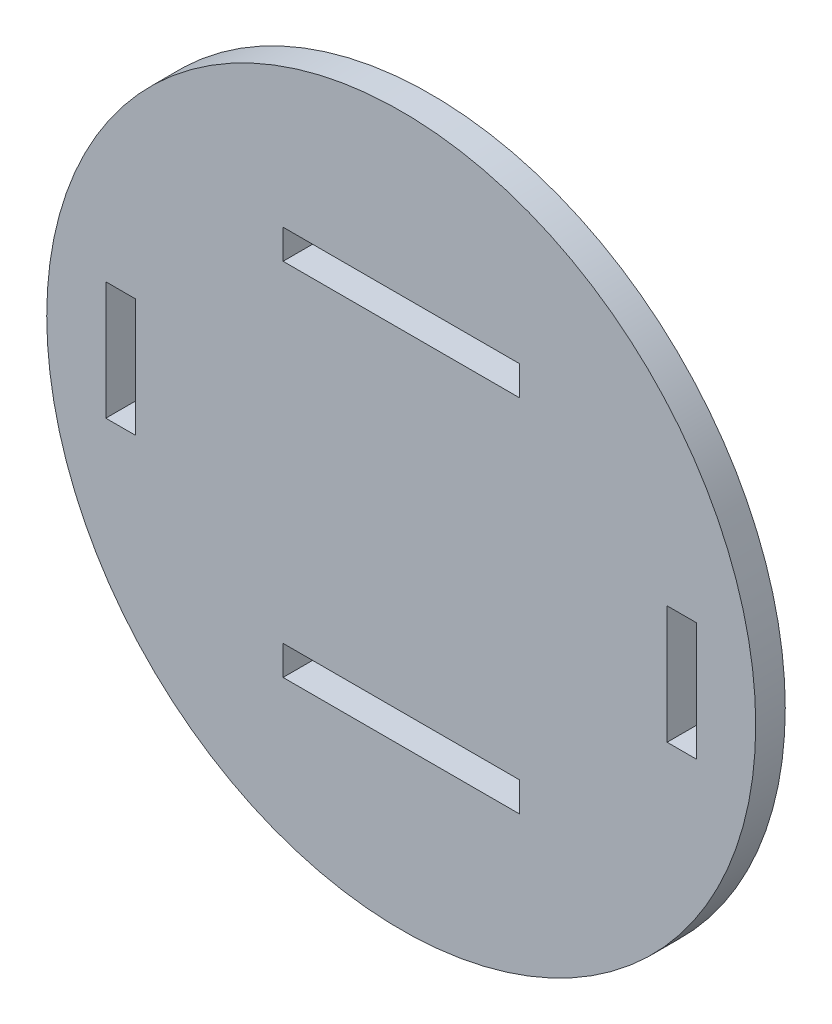
SolidWorks part; units mm, degrees
ref_plane "Front Plane" through (0, 0, 0) normal (0, 0, 1) x (1, 0, 0)
ref_plane "Top Plane" through (0, 0, 0) normal (0, 1, 0) x (1, 0, 0)
ref_plane "Right Plane" through (0, 0, 0) normal (1, 0, 0) x (0, 0, -1)
sketch "Sketch1" plane through (0, 0, 0) normal (0, 0, 1) x (1, 0, 0)
  circle A0 centre (0, 0) radius 38.1
  dimension "D1" = 76.2
extrude "Boss-Extrude1" add sketch "Sketch1" along normal blind 3.175
sketch "Sketch2" plane through (0, 0, 0) normal (0, 0, 1) x (1, 0, 0)
  line L0 (0, 0) -> (0, 17.78) construction
  line L1 (0, 17.78) -> (12.7, 17.78)
  line L2 (0, 17.78) -> (-12.7, 17.78)
  line L3 (12.7, 17.78) -> (12.7, 20.955)
  line L4 (12.7, 20.955) -> (-12.7, 20.955)
  line L5 (-12.7, 20.955) -> (-12.7, 17.78)
  line L6 (0, 0) -> (0, -17.78) construction
  line L7 (0, -17.78) -> (12.7, -17.78)
  line L8 (12.7, -17.78) -> (12.7, -20.955)
  line L9 (12.7, -20.955) -> (-12.7, -20.955)
  line L10 (-12.7, -20.955) -> (-12.7, -17.78)
  line L11 (-12.7, -17.78) -> (0, -17.78)
  line L12 (0, 0) -> (-28.575, 0) construction
  line L13 (-28.575, 0) -> (-28.575, -6.35)
  line L14 (-28.575, 0) -> (-28.575, 6.35)
  line L15 (-28.575, 6.35) -> (-31.75, 6.35)
  line L16 (-31.75, 6.35) -> (-31.75, -6.35)
  line L17 (-31.75, -6.35) -> (-28.575, -6.35)
  line L18 (0, 0) -> (28.575, 0) construction
  line L19 (28.575, 0) -> (28.575, 6.35)
  line L20 (28.575, 6.35) -> (31.75, 6.35)
  line L21 (31.75, 6.35) -> (31.75, -6.35)
  line L22 (31.75, -6.35) -> (28.575, -6.35)
  line L23 (28.575, -6.35) -> (28.575, 0)
extrude "Cut-Extrude1" cut sketch "Sketch2" along normal blind 3.175
